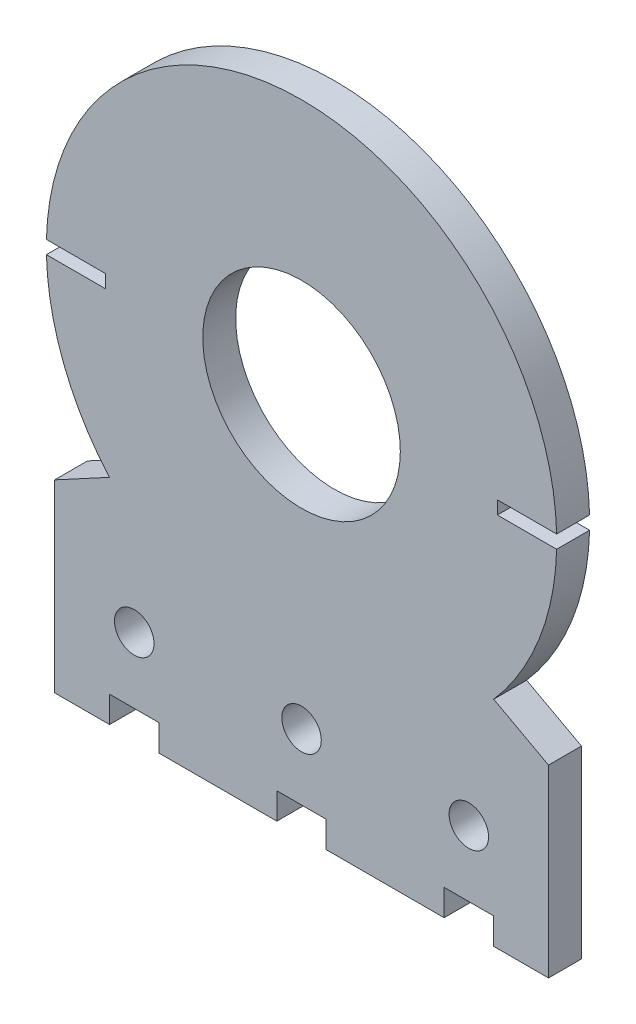
SolidWorks part; units mm, degrees
ref_plane "Front Plane" through (0, 0, 0) normal (0, 0, 1) x (1, 0, 0)
ref_plane "Top Plane" through (0, 0, 0) normal (0, 1, 0) x (1, 0, 0)
ref_plane "Right Plane" through (0, 0, 0) normal (1, 0, 0) x (0, 0, -1)
sketch "Sketch1" plane through (0, 0, 0) normal (0, 0, 1) x (1, 0, 0)
  line L0 (-7.5, -6) -> (-5.8355, -5.1)
  line L2 (-7.5, -6) -> (-7.5, -11.6)
  line L3 (-7.5, -11.6) -> (-5.83, -11.6)
  line L4 (7.5, -6) -> (7.5, -11.6)
  line L5 (7.5, -6) -> (5.8355, -5.1)
  line L7 (-5.08, -8.8) -> (0, -8.8) construction
  line L8 (0, -8.8) -> (5.08, -8.8) construction
  line L9 (5.08, -8.8) -> (7.5, -8.8) construction
  line L10 (-5.08, -8.8) -> (-7.5, -8.8) construction
  line L11 (-7.75, 0) -> (7.75, 0) construction
  line L12 (-5.9474, 0) -> (-5.9474, 0.2)
  line L13 (-5.9474, 0.2) -> (-7.7474, 0.2)
  line L14 (-5.9474, 0) -> (-5.9474, -0.2)
  line L15 (-5.9474, -0.2) -> (-7.7474, -0.2)
  line L16 (5.9474, 0) -> (5.9474, 0.2)
  line L17 (5.9474, 0.2) -> (7.7474, 0.2)
  line L18 (5.9474, 0) -> (5.9474, -0.2)
  line L19 (5.9474, -0.2) -> (7.7474, -0.2)
  line L20 (-4.33, -11.6) -> (-0.75, -11.6)
  line L22 (-5.83, -11.6) -> (-5.83, -10.8)
  line L23 (-5.83, -10.8) -> (-4.33, -10.8)
  line L24 (-4.33, -11.6) -> (-4.33, -10.8)
  line L26 (-0.75, -11.6) -> (-0.75, -10.8)
  line L27 (-0.75, -10.8) -> (0.75, -10.8)
  line L28 (0.75, -11.6) -> (0.75, -10.8)
  line L30 (4.33, -11.6) -> (4.33, -10.8)
  line L31 (4.33, -10.8) -> (5.83, -10.8)
  line L32 (5.83, -11.6) -> (5.83, -10.8)
  line L33 (0.75, -11.6) -> (4.33, -11.6)
  line L34 (5.83, -11.6) -> (7.5, -11.6)
  arc A0 (5.8355, -5.1) -> (7.7474, -0.2) centre (0, 0) ccw
  circle A1 centre (-5.08, -8.8) radius 0.6
  circle A2 centre (0, -8.8) radius 0.6
  circle A3 centre (5.08, -8.8) radius 0.6
  circle A4 centre (0, 0) radius 3
  arc A5 (-7.7474, -0.2) -> (-5.8355, -5.1) centre (0, 0) ccw
  arc A6 (7.7474, 0.2) -> (-7.7474, 0.2) centre (0, 0) ccw
  point P15 (-7.5, -8.8)
  point P22 (0, 0)
  point P44 (-5.08, -10.8)
  point P45 (0, -10.8)
  point P46 (5.08, -10.8)
  dimension "D1" = 15.5
  dimension "D6" = 1.2
  dimension "D8" = 6
  dimension "D2" = 15
  dimension "D3" = 5.6
  dimension "D4" = 0.9
  dimension "D5" = 11.6
  dimension "D7" = 5.08
  dimension "D9" = 0.2
  dimension "D10" = 1.8
  dimension "D11" = 1.5
  dimension "D12" = 0.8
extrude "Boss-Extrude1" add sketch "Sketch1" along normal mid plane 1
